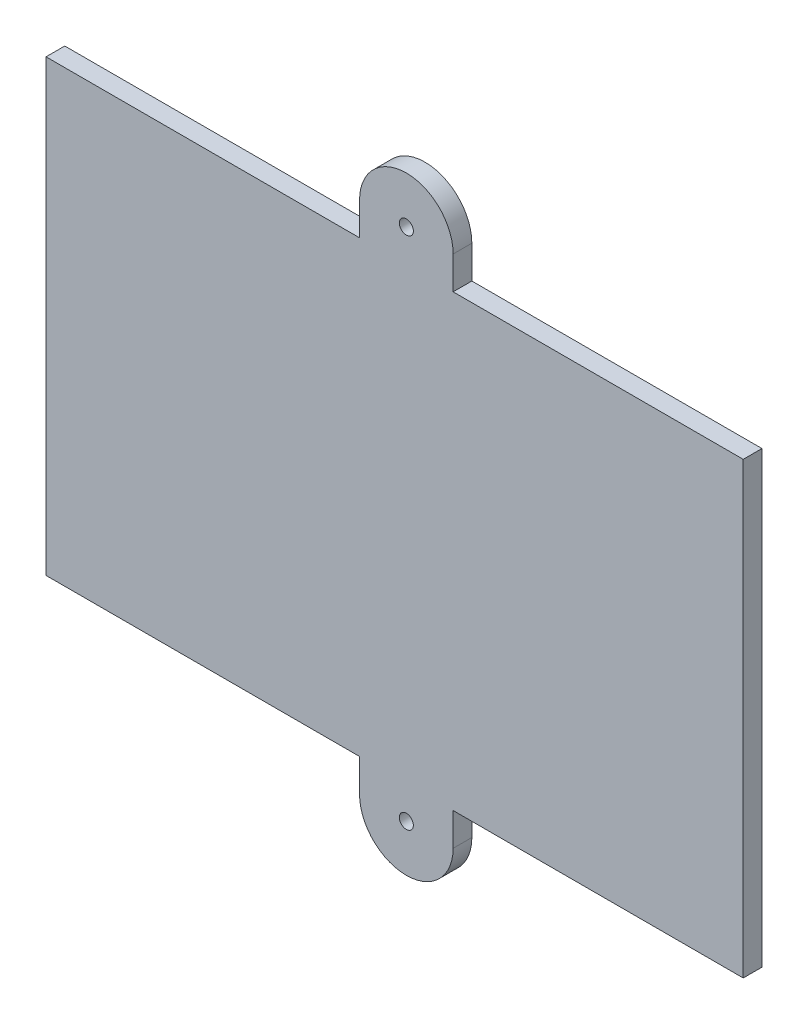
SolidWorks part; units mm, degrees
ref_plane "Front Plane" through (0, 0, 0) normal (0, 0, 1) x (1, 0, 0)
ref_plane "Top Plane" through (0, 0, 0) normal (0, 1, 0) x (1, 0, 0)
ref_plane "Right Plane" through (0, 0, 0) normal (1, 0, 0) x (0, 0, -1)
sketch "Sketch1" plane through (0, 0, 0) normal (0, 0, 1) x (1, 0, 0)
  line L0 (0, -48) -> (220.647, -48) construction
  line L1 (0, 0) -> (149, 0)
  line L2 (0, 0) -> (0, -96)
  line L3 (0, -96) -> (149, -96)
  line L4 (149, 0) -> (149, -96)
  line L5 (67, 7) -> (87, 7)
  line L6 (67, 7) -> (67, 0)
  line L7 (67, 0) -> (87, 0)
  line L8 (87, 7) -> (87, 0)
  line L9 (87, -103) -> (87, -96)
  line L10 (67, -103) -> (67, -96)
  line L11 (67, -103) -> (87, -103)
  arc A0 (67, 7) -> (87, 7) centre (77, 7) cw
  circle A1 centre (77, 7) radius 1.5
  arc A2 (67, -103) -> (87, -103) centre (77, -103) ccw
  circle A3 centre (77, -103) radius 1.5
  point P9 (77, 7)
  point P20 (0, 0)
  dimension "D6" = 3
  dimension "D1" = 96
  dimension "D2" = 149
  dimension "D3" = 20
  dimension "D4" = 7
  dimension "D5" = 72
extrude "Boss-Extrude1" add sketch "Sketch1" along normal blind 4 contours L2 L0 L4 L1 | L0 L2 L3 L4 | A1 L5 L6 L1 L8 | A1 L5 A0 | L11 A3 A2 | L11 A3 L9 L3 L10
